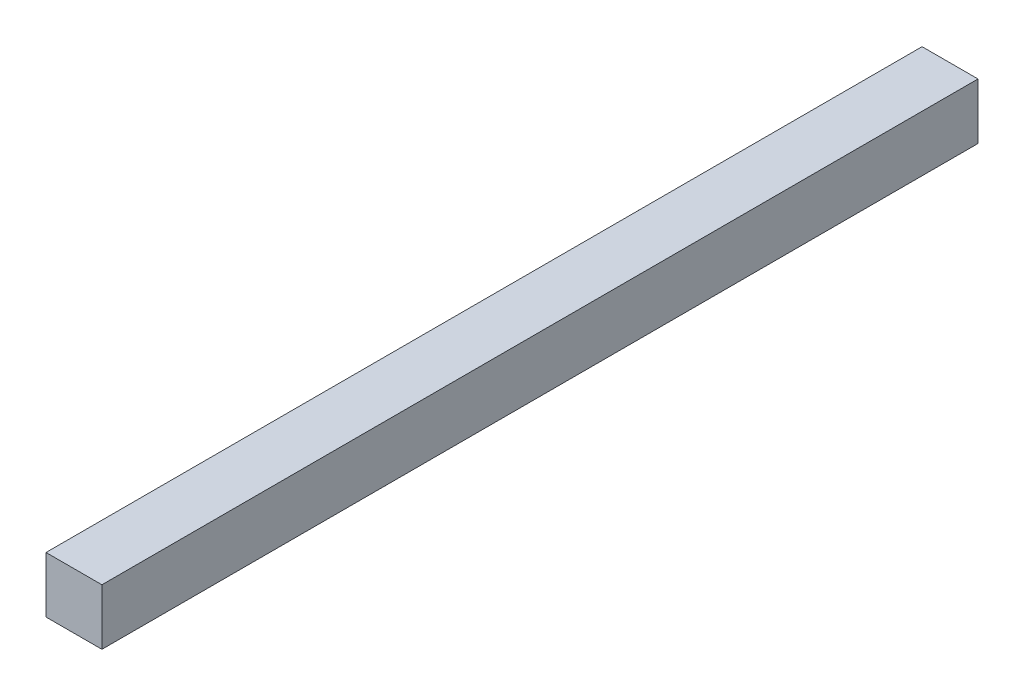
SolidWorks part; units mm, degrees
ref_plane "Front Plane" through (0, 0, 0) normal (0, 0, 1) x (1, 0, 0)
ref_plane "Top Plane" through (0, 0, 0) normal (0, 1, 0) x (1, 0, 0)
ref_plane "Right Plane" through (0, 0, 0) normal (1, 0, 0) x (0, 0, -1)
sketch "Sketch1" plane through (0, 0, 0) normal (0, 0, 1) x (1, 0, 0)
  line L1 (-19.5762, 22.7172) -> (10.4238, 22.7172)
  line L2 (-19.5762, 22.7172) -> (-19.5762, -7.2828)
  line L3 (-19.5762, -7.2828) -> (10.4238, -7.2828)
  line L4 (10.4238, 22.7172) -> (10.4238, -7.2828)
  dimension "D1" = 30
  dimension "D2" = 30
extrude "Boss-Extrude1" add sketch "Sketch1" along normal blind 470
